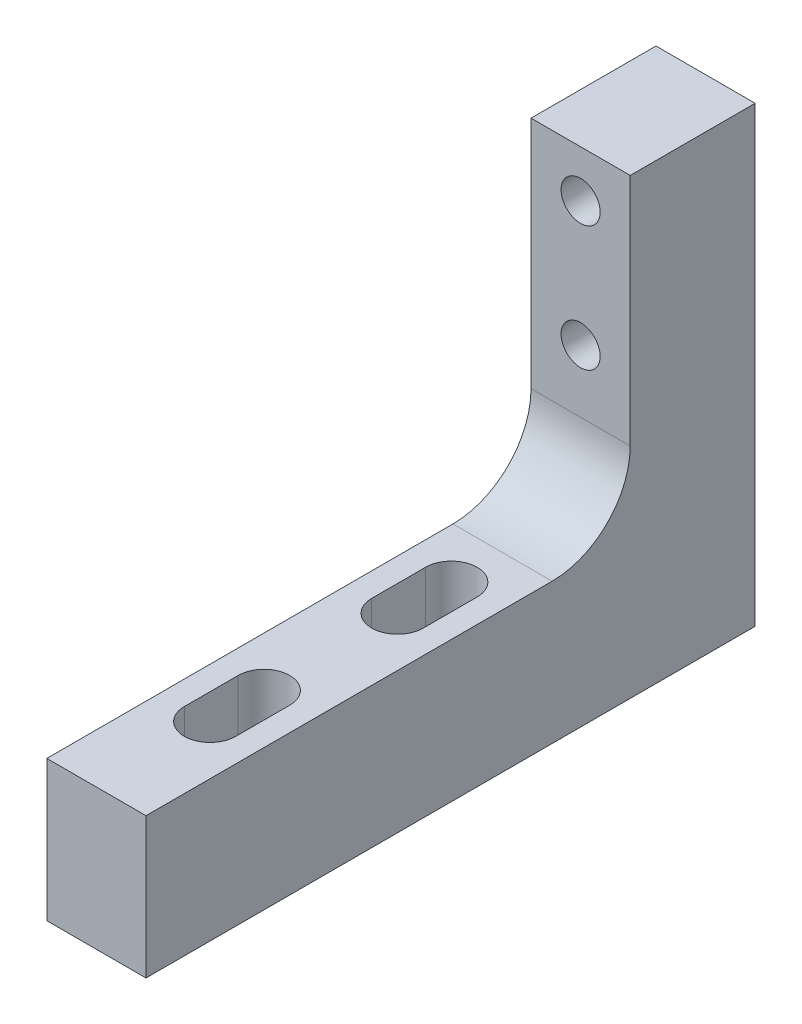
SolidWorks part; units mm, degrees
material "Low Carbon Steel"
ref_plane "Front Plane" through (0, 0, 0) normal (0, 0, 1) x (1, 0, 0)
ref_plane "Top Plane" through (0, 0, 0) normal (0, 1, 0) x (1, 0, 0)
ref_plane "Right Plane" through (0, 0, 0) normal (1, 0, 0) x (0, 0, -1)
sketch "Sketch1" plane through (0, 0, 0) normal (1, 0, 0) x (0, 0, -1)
  line L0 (0, 0) -> (78, 0)
  line L1 (78, 0) -> (78, 58)
  line L2 (78, 58) -> (62, 58)
  line L3 (62, 58) -> (62, 28)
  line L4 (52, 18) -> (0, 18)
  line L5 (0, 18) -> (0, 0)
  arc A0 (62, 28) -> (52, 18) centre (52, 28) cw
  dimension "D5" = 10
  dimension "D1" = 78
  dimension "D2" = 18
  dimension "D3" = 16
  dimension "D4" = 58
extrude "Boss-Extrude1" add sketch "Sketch1" along normal mid plane 12.7
hole_wizard "M6 Tapped Hole1" positions "Sketch3" profile "Sketch2" tap size "M6" standard "Peddi DIN"
sketch "Sketch3" plane through (0, 0, -78) normal (0, 0, -1) x (-1, 0, 0)
  line L0 (0, 9) -> (0, 36) construction
  line L1 (0, 0) -> (0, 9) construction
  line L2 (0, 36) -> (0, 52) construction
  point P0 (0, 9)
  point P2 (0, 36)
  dimension "D1" = 27
  dimension "D2" = 9
  dimension "D3" = 16
sketch "Sketch2" plane through (0, 9, -78) normal (1, 0, 0) x (0, 1, 0)
  line L0 (0, 0) -> (0, 26.9022)
  line L1 (0, 26.9022) -> (2.5, 25.4)
  line L2 (2.5, 25.4) -> (2.5, 0)
  line L5 (2.5, 0) -> (0, 0)
  line L10 (0, 26.9022) -> (-2.5, 25.4) construction
  line L11 (0, -6.35) -> (0, 107.95) construction
  dimension "Tap Drill Dia." = 5
  dimension "Tap Drill Depth" = 25.4
  dimension "Drill Angle" = 118
cosmetic thread "Hole Thread2" parameters "D1"=15.01, "D2"=6
cosmetic thread "Hole Thread3" parameters "D1"=15.01, "D2"=6
hole_wizard "M6 Tapped Hole2" positions "Sketch5" profile "Sketch6" tap size "M6" standard "Peddi DIN" end condition through all
sketch "Sketch5" plane through (0, 0, -78) normal (0, 0, -1) x (-1, 0, 0)
  point P0 (0, 52)
sketch "Sketch6" plane through (0, 52, -78) normal (1, 0, 0) x (0, 1, 0)
  line L0 (0, 0) -> (0, 78)
  line L1 (0, 78) -> (2.5, 78)
  line L2 (2.5, 78) -> (2.5, 0)
  line L5 (2.5, 0) -> (0, 0)
  line L11 (0, -6.35) -> (0, 107.95) construction
  dimension "Thru Tap Drill Dia." = 5
  dimension "Thru Tap Drill Depth" = 78
cosmetic thread "Hole Thread1" parameters "D2"=6
sketch "Sketch4" plane through (0, 18, 0) normal (0, 1, 0) x (1, 0, 0)
  line L0 (0, 45.45) -> (0, 38.55) construction
  line L1 (3.3, 45.45) -> (3.3, 38.55)
  line L2 (-3.3, 45.45) -> (-3.3, 38.55)
  line L3 (0, 21.45) -> (0, 14.55) construction
  line L4 (3.3, 21.45) -> (3.3, 14.55)
  line L5 (-3.3, 21.45) -> (-3.3, 14.55)
  line L6 (0, 42) -> (0, 18) construction
  line L7 (0, 0) -> (0, 18) construction
  line L8 (6.35, 0) -> (-6.35, 0) construction
  line L9 (6.35, 78) -> (-6.35, 78) construction
  arc A0 (3.3, 45.45) -> (-3.3, 45.45) centre (0, 45.45) ccw
  arc A1 (-3.3, 38.55) -> (3.3, 38.55) centre (0, 38.55) ccw
  arc A2 (3.3, 21.45) -> (-3.3, 21.45) centre (0, 21.45) ccw
  arc A3 (-3.3, 14.55) -> (3.3, 14.55) centre (0, 14.55) ccw
  point P3 (0, 42)
  point P8 (0, 18)
  dimension "D5" = 13.5
  dimension "D1" = 6.6
  dimension "D2" = 6.9
  dimension "D3" = 24
  dimension "D4" = 36
extrude "Cut-Extrude1" cut sketch "Sketch4" against normal through all
ref_plane "Plane1" through (0, 0, -38.55) normal (0, 0, -1) x (-1, 0, 0)
ref_plane "Plane2" through (0, 0, -21.45) normal (0, 0, 1) x (1, 0, 0)
other "Freeze***"
equation "\".5i\"=0.5"
